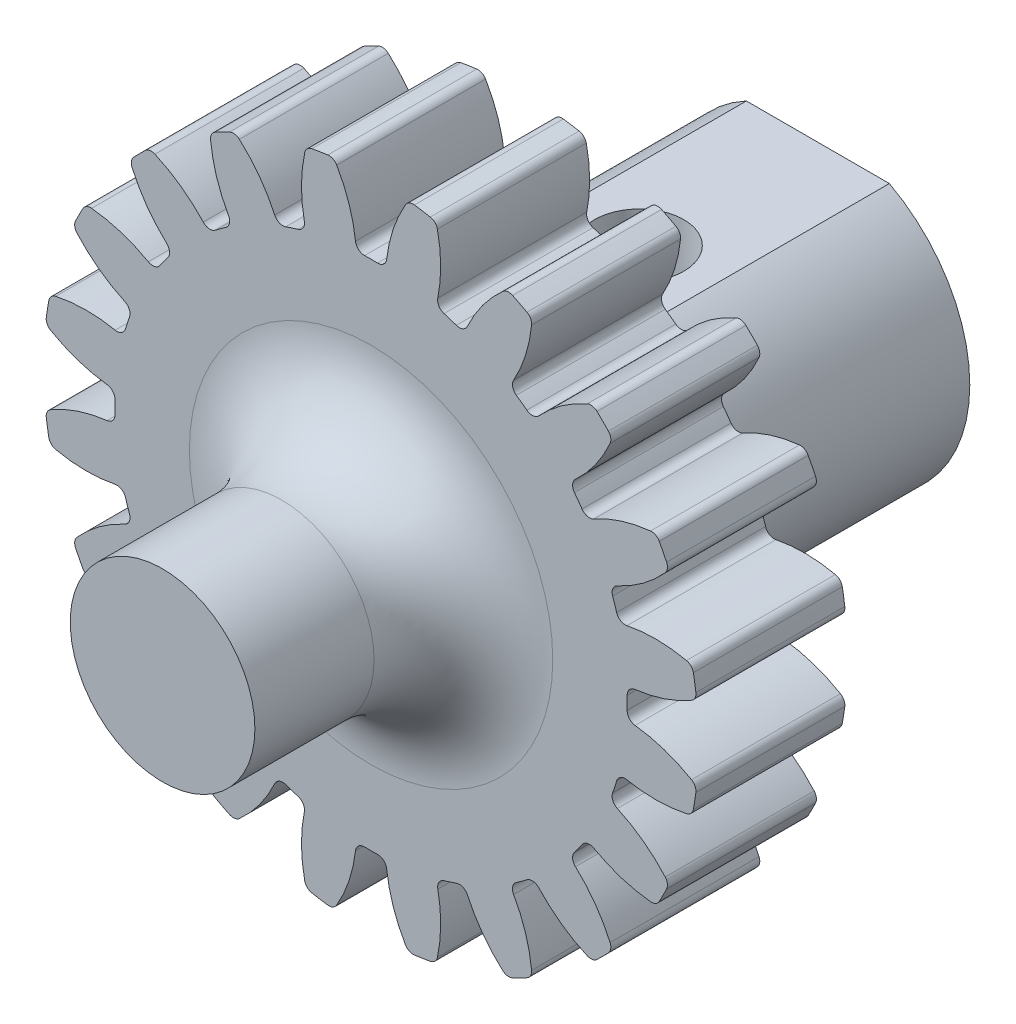
SolidWorks part; units mm, degrees
ref_plane "Front Plane" through (0, 0, 0) normal (0, 0, 1) x (1, 0, 0)
ref_plane "Top Plane" through (0, 0, 0) normal (0, 1, 0) x (1, 0, 0)
ref_plane "Right Plane" through (0, 0, 0) normal (1, 0, 0) x (0, 0, -1)
sketch "Sketch1" plane through (0, 0, 0) normal (0, 0, 1) x (1, 0, 0)
  circle A2 centre (0, 0) radius 10
  circle A3 centre (0, 0) radius 11
  circle A4 centre (0, 0) radius 8.6
  dimension "D1" = 20
  dimension "D2" = 22
  dimension "D3" = 2.4
extrude "Boss-Extrude1" add sketch "Sketch1" along normal mid plane 5 contours A3
sketch "Sketch3" plane through (0, 0, 2.5) normal (0, 0, 1) x (1, 0, 0)
  line L0 (0, 0) -> (0, 11) construction
  line L1 (-0.7846, 9.9692) -> (0.7846, 9.9692) construction
  line L2 (0, 0) -> (-0.499, 8.5855) construction
  line L3 (0, 7.8135) -> (-1.49, 11.9071) construction
  line L4 (0, 0) -> (1.7208, 10.8646) construction
  line L5 (0.7846, 9.9692) -> (2.3345, 9.7237) construction
  circle A0 centre (0, 0) radius 11 construction
  arc A1 (-2.0035, 11.8316) -> (-0.499, 8.5855) centre (-5.3628, 8.3028) cw
  arc A2 (2.0035, 11.8316) -> (0.499, 8.5855) centre (5.3628, 8.3028) ccw
  circle A3 centre (0, 0) radius 8.6 construction
  arc A4 (0.499, 8.5855) -> (-0.499, 8.5855) centre (0, 0) ccw
  circle A5 centre (0, 0) radius 10 construction
  circle A6 centre (0, 0) radius 11 construction
  circle A7 centre (0, 0) radius 12
  arc A8 (2.0035, 11.8316) -> (-2.0035, 11.8316) centre (0, 0) ccw
  dimension "D2" = 20
  dimension "D3" = 9
  dimension "D1" = 1
extrude "Cut-Extrude1" cut sketch "Sketch3" against normal through all both and the other way through all
fillet "Fillet1" radius 0.3 4 edges at (0.499, 8.5855, 0) (-0.499, 8.5855, 0) (1.2584, 10.9278, 0) (-1.2584, 10.9278, 0)
pattern_circular "CirPattern1" count 20 over 360 about axis through (0, 0, 0) along (0, 0, 1) of "Cut-Extrude1", "Fillet1"
sketch "Sketch4" plane through (0, 0, 2.5) normal (0, 0, 1) x (1, 0, 0)
  line L0 (-1.833, 2.5) -> (1.833, 2.5)
  arc A0 (-1.833, 2.5) -> (1.833, 2.5) centre (0, 0) ccw
  dimension "D1" = 6.2
  dimension "D2" = 2.5
extrude "Cut-Extrude2" cut sketch "Sketch4" against normal through all both
sketch "Sketch11" plane through (0, 0, -2.5) normal (0, 0, -1) x (-1, 0, 0)
  line L1 (-1.833, 2.5) -> (1.833, 2.5) construction
  line L2 (2.4, 4.5) -> (-2.4, 4.5)
  line L3 (2.4, 4.5) -> (-2.4, 4.5)
  line L4 (-1.833, 2.5) -> (1.833, 2.5)
  arc A1 (-1.833, 2.5) -> (1.833, 2.5) centre (0, 0) ccw construction
  arc A2 (-2.4, 4.5) -> (2.4, 4.5) centre (0, 0) ccw
  arc A3 (-2.4, 4.5) -> (2.4, 4.5) centre (0, 0) ccw
  arc A4 (-1.833, 2.5) -> (1.833, 2.5) centre (0, 0) ccw
  dimension "D2" = 3.1
  dimension "D1" = 2
extrude "Back Shaft" add sketch "Sketch11" along normal blind 10
sketch "Sketch12" plane through (0, 4.5, 0) normal (0, 1, 0) x (1, 0, 0)
  line L0 (0, 12.5) -> (0, 6.5) construction
  line L1 (-2.4, 12.5) -> (2.4, 12.5) construction
  circle A0 centre (0, 6.5) radius 1.5
  dimension "D2" = 3
  dimension "D1" = 6
extrude "Cut-Extrude4" cut sketch "Sketch12" against normal blind 20
sketch "Sketch15" plane through (0, 0, 2.5) normal (0, 0, 1) x (1, 0, 0)
  circle A0 centre (0, 0) radius 3.1
extrude "Front Shaft" add sketch "Sketch15" along normal blind 7 and the other way blind 2 contours A0
fillet "Fillet3" radius 3 1 edges at (3.1, 0, 2.5)
sketch "Sketch16" plane through (0, 0, -12.5) normal (0, 0, -1) x (-1, 0, 0)
  circle A0 centre (0, 0) radius 3.2
  dimension "D1" = 6.4
extrude "Cut-Extrude5" cut sketch "Sketch16" against normal blind 2
sketch "Sketch17" plane through (0, 0, -10.5) normal (0, 0, -1) x (-1, 0, 0)
  line L0 (-1.833, 2.5) -> (-2.3414, 2.5)
  line L1 (-2.3414, 2.5) -> (2.0534, 2.5)
  circle A0 centre (0, 0) radius 3.2
  circle M1 centre (0, 0) radius 3.2
  arc M2 (1.833, 2.5) -> (-1.833, 2.5) centre (0, 0) cw
  line M3 (-1.833, 2.5) -> (1.833, 2.5)
  dimension "D1" = 6.4
extrude "Cut-Extrude15" cut sketch "Sketch17" against normal blind 11 contours L1 L0 M2 M1 | M2 M3
fillet "Fillet4" radius 1 1 edges at (0, -5.1, -2.5)
equation "\"Module\"= 1mm"
equation "\"Number of Teeth\"= 20"
equation "\"D1@Sketch1\"=\"Module\" * \"Number of Teeth\""
equation "\"D2@Sketch1\"=(\"Number of Teeth\" + 2) * \"Module\""
equation "\"D3@Sketch1\"=\"Module\" * if( \"Module\"=>1.25,2.25,2.4)"
equation "\"D3@Sketch3\"=180 / \"Number of Teeth\""
equation "\"D1@Fillet1\"=0.3 * \"Module\""
equation "\"D1@CirPattern1\"=\"Number of Teeth\""
